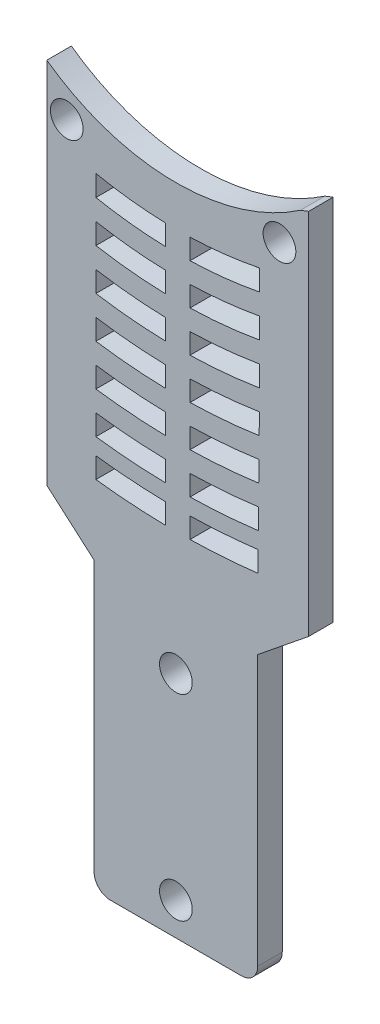
SolidWorks part; units mm, degrees
ref_plane "Front Plane" through (0, 0, 0) normal (0, 0, 1) x (1, 0, 0)
ref_plane "Top Plane" through (0, 0, 0) normal (0, 1, 0) x (1, 0, 0)
ref_plane "Right Plane" through (0, 0, 0) normal (1, 0, 0) x (0, 0, -1)
sketch "Sketch1" plane through (0, 0, 0) normal (0, 0, 1) x (1, 0, 0)
  line L0 (-16, -22.5) -> (-10.2251, -27.5247)
  line L1 (16, -22.5) -> (-16, -22.5)
  line L2 (16, -22.5) -> (16, 22.5)
  line L3 (16, 22.5) -> (-16, 22.5)
  line L4 (-16, -22.5) -> (-16, 22.5)
  line L5 (16, -22.5) -> (-16, 22.5) construction
  line L6 (16, 22.5) -> (-16, -22.5) construction
  line L7 (9.7749, -62.5247) -> (-10.2251, -62.5247)
  line L8 (9.7749, -62.5247) -> (9.7749, -27.5247)
  line L9 (9.7749, -27.5247) -> (-10.2251, -27.5247)
  line L10 (-10.2251, -62.5247) -> (-10.2251, -27.5247)
  line L11 (9.7749, -62.5247) -> (-10.2251, -27.5247) construction
  line L12 (9.7749, -27.5247) -> (-10.2251, -62.5247) construction
  line L13 (9.7749, -27.5247) -> (16, -22.5)
  line L14 (0, 22.5) -> (0, 62.5)
  circle A0 centre (0, 62.5) radius 43.0813
  point P0 (0, 0)
  point P6 (-0.2251, -45.0247)
extrude "Boss-Extrude1" add sketch "Sketch1" along normal blind 3 contours A0 L4 L1 L2 | L10 L7 L8 L9 | L9 L13 L1 L0
fillet "Fillet5" radius 2 2 edges at (-10.2251, -62.5247, 1.5) (9.7749, -62.5247, 1.5)
sketch "Sketch2" plane through (0, 0, 3) normal (0, 0, 1) x (1, 0, 0)
  point P7 (-0.2251, -32.5247)
  point P8 (-0.2251, -57.5247)
hole_wizard "#97 (0.0059) Diameter Hole2" positions "3DSketch4" profile "Sketch6" hole size "#97" standard "ANSI Inch" end condition through all
sketch3d "3DSketch4"
  point P0 (-0.2251, -57.5247, 3)
sketch "Sketch6" plane through (-0.2251, -57.5247, 3) normal (1, 0, 0) x (0, -1, 0)
  line L0 (0, 0) -> (0, 3)
  line L1 (0, 3) -> (1.5, 3)
  line L2 (1.5, 3) -> (1.5, 0)
  line L5 (1.5, 0) -> (0, 0)
  line L11 (0, -6.35) -> (0, 107.95) construction
  dimension "Thru Hole Dia." = 3
  dimension "Thru Hole Depth" = 3
hole_wizard "#97 (0.0059) Diameter Hole4" positions "3DSketch6" profile "Sketch8" hole size "#97" standard "ANSI Inch" end condition through all
sketch3d "3DSketch6"
  point P0 (-0.2251, -32.5247, 3)
sketch "Sketch8" plane through (-0.2251, -32.5247, 3) normal (1, 0, 0) x (0, -1, 0)
  line L0 (0, 0) -> (0, 3)
  line L1 (0, 3) -> (1.5, 3)
  line L2 (1.5, 3) -> (1.5, 0)
  line L5 (1.5, 0) -> (0, 0)
  line L11 (0, -6.35) -> (0, 107.95) construction
  dimension "Thru Hole Dia." = 3
  dimension "Thru Hole Depth" = 3
sketch "Sketch12" plane through (0, 0, 3) normal (0, 0, 1) x (1, 0, 0)
  point P6 (-13.9717, 19.6477)
  point P9 (13.9324, 19.6445)
hole_wizard "#97 (0.0059) Diameter Hole6" positions "3DSketch9" profile "Sketch13" hole size "#97" standard "ANSI Inch" end condition through all
sketch3d "3DSketch9"
  point P0 (-13.9717, 19.6477, 3)
sketch "Sketch13" plane through (-13.9717, 19.6477, 3) normal (1, 0, 0) x (0, -1, 0)
  line L0 (0, 0) -> (0, 3)
  line L1 (0, 3) -> (1.5, 3)
  line L2 (1.5, 3) -> (1.5, 0)
  line L5 (1.5, 0) -> (0, 0)
  line L11 (0, -6.35) -> (0, 107.95) construction
  dimension "Thru Hole Dia." = 3
  dimension "Thru Hole Depth" = 3
hole_wizard "#97 (0.0059) Diameter Hole7" positions "3DSketch10" profile "Sketch14" hole size "#97" standard "ANSI Inch" end condition through all
sketch3d "3DSketch10"
  point P0 (13.9324, 19.6445, 3)
sketch "Sketch14" plane through (13.9324, 19.6445, 3) normal (1, 0, 0) x (0, -1, 0)
  line L0 (0, 0) -> (0, 3)
  line L1 (0, 3) -> (1.5, 3)
  line L2 (1.5, 3) -> (1.5, 0)
  line L5 (1.5, 0) -> (0, 0)
  line L11 (0, -6.35) -> (0, 107.95) construction
  dimension "Thru Hole Dia." = 3
  dimension "Thru Hole Depth" = 3
sketch "Sketch15" plane through (0, 0, 3) normal (0, 0, 1) x (1, 0, 0)
  line L0 (0, 19.4187) -> (-0.2251, -62.5247)
  line L1 (7.7749, -62.5247) -> (-8.2251, -62.5247) construction
  line L2 (0, 0) -> (-1.5, 0)
  line L3 (-1.5, 0) -> (1.4637, 0)
  line L4 (-1.5, 0) -> (-1.5, -62.5247)
  line L5 (-1.5, -62.5247) -> (1.5, -62.5247)
  line L6 (1.5, -62.5247) -> (1.5, 19.4448)
  line L7 (-1.5, 0) -> (-1.5, 19.4448)
  line L8 (0, 0) -> (10, 0)
  line L9 (0, 0) -> (-10, 0)
  line L10 (-10, 20.5953) -> (-10, -62.5247)
  line L11 (-10, -62.5247) -> (9.3443, -61.7644)
  line L12 (9.3443, -61.7644) -> (10, 0)
  line L13 (10, 0) -> (10, 20.5953)
  arc A0 (-16, 22.5) -> (16, 22.5) centre (0, 62.5) ccw construction
  circle A1 centre (0, 62.5) radius 50
  circle A2 centre (0, 62.5) radius 52.5
  circle A3 centre (0, 62.5) radius 55
  circle A4 centre (0, 62.5) radius 57.5
  circle A5 centre (0, 62.5) radius 60
  circle A6 centre (0, 62.5) radius 62.5
  circle A7 centre (0, 62.5) radius 65
  circle A8 centre (0, 62.5) radius 67.5
  circle A9 centre (0, 62.5) radius 70
  circle A10 centre (0, 62.5) radius 72.5
  circle A11 centre (0, 62.5) radius 75
  circle A12 centre (0, 62.5) radius 77.5
  circle A13 centre (0, 62.5) radius 79.5
  circle A14 centre (0, 62.5) radius 82
  circle A15 centre (0, 62.5) radius 84.5
  arc A16 (7.7749, -62.5247) -> (9.7749, -60.5247) centre (7.7749, -60.5247) ccw construction
extrude "Cut-Extrude1" cut sketch "Sketch15" against normal blind 3 contours L6 A2 L13 A1 | L10 A2 L7 A1 | L10 A4 L7 A3 | L6 A4 L13 A3 | L10 A6 L7 A5 | L6 A6 L13 A5 | L10 A8 L4 A7 | L6 A8 L12 A7 | L10 A10 L4 A9 | L6 A10 L12 A9 | L10 A12 L4 A11 | L10 A14 L4 A13 | L6 A14 L12 A13 | L6 A12 L12 A11
sketch "Sketch17" plane through (0, 0, 3) normal (0, 0, 1) x (1, 0, 0)
  line L1 (-16, 22.5) -> (-16, 24.42)
  line L2 (-16, 24.42) -> (15.6528, 24.42)
  line L3 (-0.2251, -62.5247) -> (-0.0097, 44.4751)
  line L4 (7.7749, -62.5247) -> (-8.2251, -62.5247) construction
  circle A0 centre (0, 62.5) radius 43.08
  circle A1 centre (13.9324, 19.6445) radius 1.5
  circle A2 centre (-13.9717, 19.6477) radius 1.5
  circle A3 centre (-0.2251, -32.5247) radius 1.5
  circle A4 centre (-0.2251, -57.5247) radius 1.5
  circle A5 centre (-0.0097, 44.4751) radius 27.1771
extrude "Boss-Extrude3" add sketch "Sketch17" against normal up to vertex (3 mm away) contours A5 A2 | A2 A5 | A5 A1 | A1 A5 | L3 A3 | L3 A3 | L3 A4 | L3 A4
sketch "Sketch18" plane through (0, 0, 3) normal (0, 0, 1) x (1, 0, 0)
  line L0 (-0.2251, -62.5247) -> (-0.2251, 44.4753)
  line L1 (7.7749, -62.5247) -> (-8.2251, -62.5247) construction
  line L2 (-16, 22.5) -> (-16, 27.5)
  line L3 (-16, 27.5) -> (16, 27.5)
  line L4 (16, 27.5) -> (16, 22.5)
  circle A0 centre (-0.2251, 44.4753) radius 23.4822
  circle A1 centre (-0.2251, 44.4753) radius 27.0511
  circle A2 centre (0, 62.5) radius 43.0813
extrude "Cut-Extrude3" cut sketch "Sketch18" against normal blind 3 contours A2 L0 A1 | A2 A1 L0
sketch "Sketch19" plane through (0, 0, 3) normal (0, 0, 1) x (1, 0, 0)
  line L0 (-0.2251, -62.5247) -> (-0.2251, -58.5247)
  line L1 (7.7749, -62.5247) -> (-8.2251, -62.5247) construction
  line L2 (-0.2251, -58.5247) -> (-0.2251, -34.5247)
  circle A0 centre (-0.2251, -34.5247) radius 2
  circle A1 centre (-0.2251, -58.5247) radius 2
extrude "Cut-Extrude4" cut sketch "Sketch19" against normal blind 10
sketch "Sketch20" plane through (0, 0, 0) normal (0, 0, -1) x (-1, 0, 0)
  line L0 (0.2251, -62.5247) -> (0.563, 17.4263)
  line L1 (-7.7749, -62.5247) -> (8.2251, -62.5247) construction
  line L2 (0.563, 17.4263) -> (13.563, 17.4263)
  line L3 (0.563, 17.4263) -> (-12.437, 17.4263)
  arc A0 (-14.9959, 22.1128) -> (16, 22.5) centre (0.2251, 44.4753) ccw construction
  circle A1 centre (13.563, 17.4263) radius 2
  circle A2 centre (-12.437, 17.4263) radius 2
extrude "Cut-Extrude6" cut sketch "Sketch20" against normal blind 10
